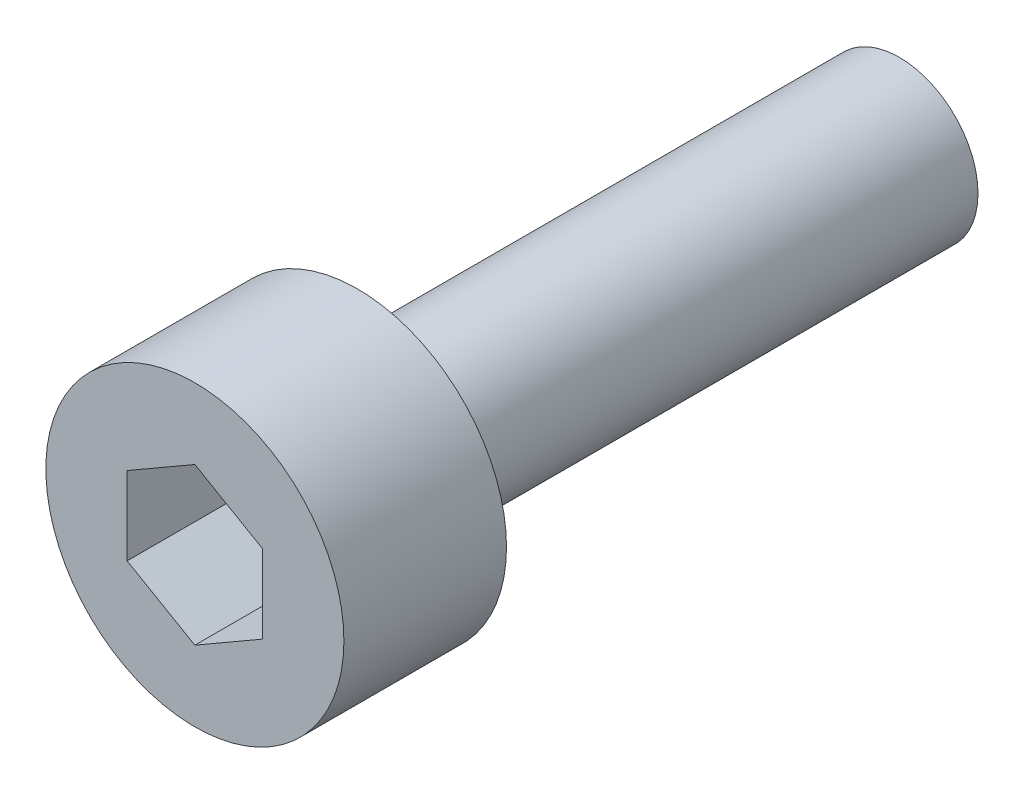
SolidWorks part; units mm, degrees
ref_plane "前视基准面" through (0, 0, 0) normal (0, 0, 1) x (1, 0, 0)
ref_plane "上视基准面" through (0, 0, 0) normal (0, 1, 0) x (1, 0, 0)
ref_plane "右视基准面" through (0, 0, 0) normal (1, 0, 0) x (0, 0, -1)
other "Configuration Table"
sketch "草图1" plane through (0, 0, 0) normal (0, 0, 1) x (1, 0, 0)
  circle A0 centre (0, 0) radius 1.45
extrude "Shank_threads_simplified" add sketch "草图1" against normal blind 10
sketch "草图2" plane through (0, 0, 0) normal (0, 0, 1) x (1, 0, 0)
  circle A0 centre (0, 0) radius 2.75
extrude "Socket_head" add sketch "草图2" along normal blind 3
ref_plane "Plane_z_3_2" through (0, 0, 3) normal (0, 0, 1) x (1, 0, 0)
sketch "草图3" plane through (0, 0, 3) normal (0, 0, 1) x (1, 0, 0)
  line L0 (1.25, 0.7217) -> (0, 1.4434)
  line L1 (0, 1.4434) -> (-1.25, 0.7217)
  line L2 (-1.25, 0.7217) -> (-1.25, -0.7217)
  line L3 (-1.25, -0.7217) -> (0, -1.4434)
  line L4 (0, -1.4434) -> (1.25, -0.7217)
  line L5 (1.25, -0.7217) -> (1.25, 0.7217)
extrude "Hex_socket" cut sketch "草图3" against normal blind 1.95
